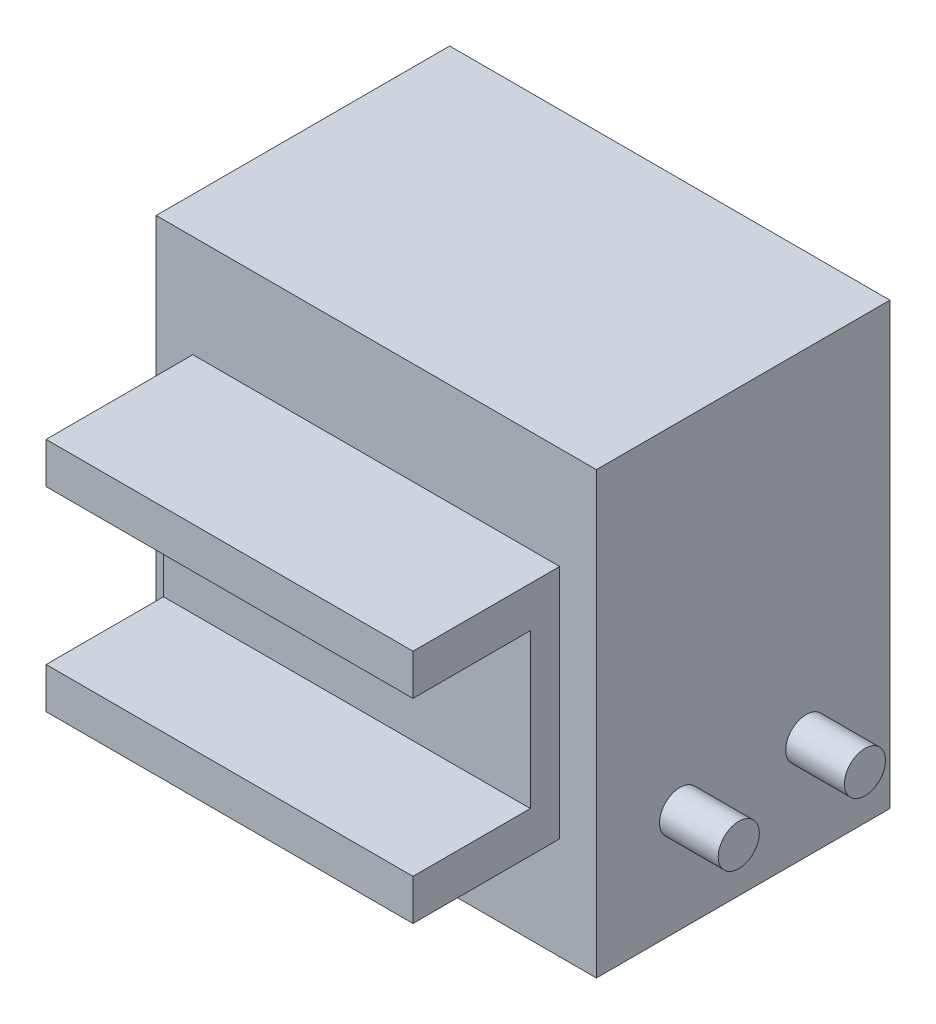
SolidWorks part; units mm, degrees
ref_plane "前视基准面" through (0, 0, 0) normal (0, 0, 1) x (1, 0, 0)
ref_plane "上视基准面" through (0, 0, 0) normal (0, 1, 0) x (1, 0, 0)
ref_plane "右视基准面" through (0, 0, 0) normal (1, 0, 0) x (0, 0, -1)
sketch "草图1" plane through (0, 0, 0) normal (0, 1, 0) x (1, 0, 0)
  line L1 (-15.3715, 12.1835) -> (14.6285, 12.1835)
  line L2 (-15.3715, 12.1835) -> (-15.3715, -7.8165)
  line L3 (-15.3715, -7.8165) -> (14.6285, -7.8165)
  line L4 (14.6285, 12.1835) -> (14.6285, -7.8165)
  dimension "D1" = 30
  dimension "D2" = 20
extrude "凸台-拉伸1" add sketch "草图1" along normal blind 30
sketch "草图3" plane through (0, 0, 7.8165) normal (0, 0, 1) x (1, 0, 0)
  line L4 (12.1285, 23.035) -> (-12.8715, 23.035)
  line L5 (-12.8715, 23.035) -> (-12.8715, 6.965)
  line L7 (-12.8715, 6.965) -> (12.1285, 6.965)
  line L8 (12.1285, 6.965) -> (12.1285, 23.035)
  line L9 (14.6285, 30) -> (14.6285, 0) construction
  line L10 (-15.3715, 0) -> (14.6285, 0) construction
  dimension "D1" = 2.5
  dimension "D2" = 25
  dimension "D3" = 6.965
  dimension "D4" = 16.07
extrude "凸台-拉伸2" add sketch "草图3" along normal blind 10
sketch "草图7" plane through (-12.8715, 0, 0) normal (-1, 0, 0) x (0, 0, 1)
  line L0 (17.8165, 20.25) -> (9.8165, 20.25)
  line L1 (17.8165, 23.035) -> (17.8165, 6.965) construction
  line L2 (9.8165, 20.25) -> (9.8165, 9.75)
  line L3 (9.8165, 9.75) -> (17.8165, 9.75)
  line L4 (17.8165, 9.75) -> (17.8165, 20.25)
  line L5 (17.8165, 23.035) -> (7.8165, 23.035) construction
  dimension "D1" = 10.5
  dimension "D2" = 8
  dimension "D3" = 2.785
extrude "切除-拉伸1" cut sketch "草图7" against normal through all
sketch "草图9" plane through (-15.3715, 0, 0) normal (-1, 0, 0) x (0, 0, 1)
  line L0 (-10.6835, 28) -> (6.3165, 28)
  line L1 (6.3165, 28) -> (6.3165, 2)
  line L2 (6.3165, 2) -> (-10.6835, 2)
  line L3 (-10.6835, 2) -> (-10.6835, 28)
  line L4 (7.8165, 30) -> (7.8165, 0) construction
  line L5 (-12.1835, 0) -> (7.8165, 0) construction
  dimension "D1" = 26
  dimension "D2" = 17
  dimension "D3" = 1.5
  dimension "D4" = 2
extrude "切除-拉伸2" cut sketch "草图9" against normal blind 25
sketch "草图11" plane through (14.6285, 0, 0) normal (1, 0, 0) x (0, 0, -1)
  line L0 (-7.8165, 0) -> (12.1835, 0) construction
  line L1 (-7.8165, 30) -> (-7.8165, 0) construction
  circle A0 centre (-2.1165, 7) radius 1.4
  circle A1 centre (6.4835, 7) radius 1.4
  dimension "D1" = 2.8
  dimension "D5" = 2.8
  dimension "D2" = 8.6
  dimension "D3" = 7
  dimension "D4" = 5.7
extrude "凸台-拉伸3" add sketch "草图11" along normal blind 4
sketch "草图12" plane through (0, 0, -12.1835) normal (0, 0, -1) x (-1, 0, 0)
  line L0 (-14.6285, 0) -> (15.3715, 0) construction
  line L1 (-14.6285, 30) -> (-14.6285, 0) construction
  circle A0 centre (-3.9285, 7) radius 1.4
  circle A1 centre (4.6715, 7) radius 1.4
  dimension "D1" = 2.8
  dimension "D5" = 2.8
  dimension "D2" = 8.6
  dimension "D3" = 7
  dimension "D4" = 10.7
extrude "凸台-拉伸4" add sketch "草图12" along normal blind 4
